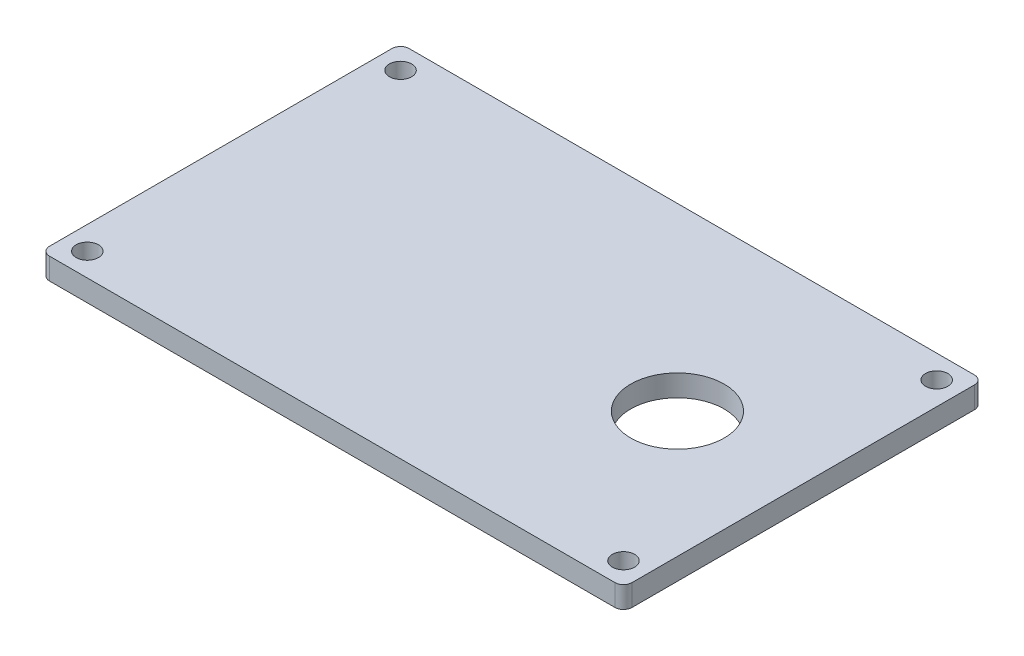
SolidWorks part; units mm, degrees
ref_plane "前基準面" through (0, 0, 0) normal (0, 0, 1) x (1, 0, 0)
ref_plane "上基準面" through (0, 0, 0) normal (0, 1, 0) x (1, 0, 0)
ref_plane "右基準面" through (0, 0, 0) normal (1, 0, 0) x (0, 0, -1)
sketch "草圖1" plane through (0, 0, 0) normal (0, 1, 0) x (1, 0, 0)
  line L1 (-39.3, -25) -> (39.3, -25)
  line L2 (-40.5, -23.8) -> (-40.5, 23.8)
  line L3 (-39.3, 25) -> (39.3, 25)
  line L4 (40.5, -23.8) -> (40.5, 23.8)
  line L5 (-40.5, -25) -> (40.5, 25) construction
  line L6 (-40.5, 25) -> (40.5, -25) construction
  arc A0 (-39.3, -25) -> (-40.5, -23.8) centre (-39.3, -23.8) cw
  arc A1 (39.3, -25) -> (40.5, -23.8) centre (39.3, -23.8) ccw
  arc A2 (39.3, 25) -> (40.5, 23.8) centre (39.3, 23.8) cw
  arc A3 (-40.5, 23.8) -> (-39.3, 25) centre (-39.3, 23.8) cw
  circle A4 centre (-37.275, 21.775) radius 1.55
  circle A5 centre (37.275, 21.775) radius 1.55
  circle A6 centre (37.275, -21.775) radius 1.55
  circle A7 centre (-37.275, -21.775) radius 1.55
  point P0 (0, 0)
  dimension "D3" = 1.2
  dimension "D4" = 3.1
  dimension "D1" = 81
  dimension "D2" = 50
  dimension "D5" = 3.225
  dimension "D6" = 3.225
  dimension "D7" = 3.225
  dimension "D8" = 3.225
extrude "填料-伸長1" add sketch "草圖1" along normal blind 3
sketch "草圖2" plane through (0, 0, 0) normal (0, -1, 0) x (1, 0, 0)
  line L0 (40.5, 23.8) -> (40.5, -23.8) construction
  circle A0 centre (23, 0) radius 6.5
  dimension "D1" = 13
  dimension "D2" = 17.5
extrude "除料-伸長1" cut sketch "草圖2" against normal through all
